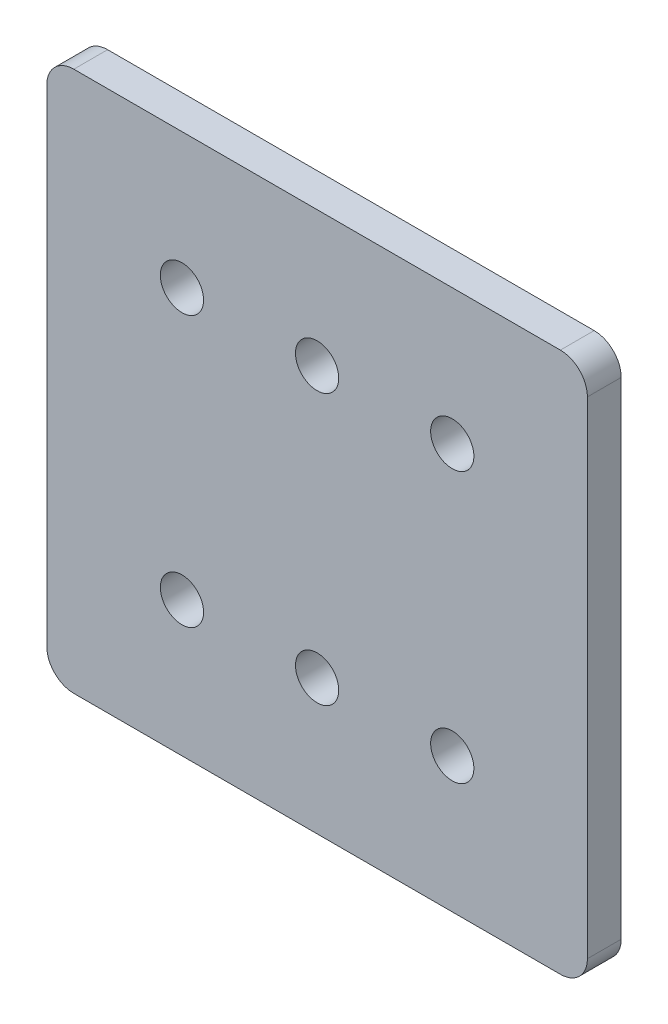
SolidWorks part; units mm, degrees
ref_plane "Front Plane" through (0, 0, 0) normal (0, 0, 1) x (1, 0, 0)
ref_plane "Top Plane" through (0, 0, 0) normal (0, 1, 0) x (1, 0, 0)
ref_plane "Right Plane" through (0, 0, 0) normal (1, 0, 0) x (0, 0, -1)
sketch "Sketch1" plane through (0, 0, 0) normal (0, 0, 1) x (1, 0, 0)
  line L1 (-25.4, -25.4) -> (25.4, -25.4)
  line L2 (-25.4, -25.4) -> (-25.4, 25.4)
  line L3 (-25.4, 25.4) -> (25.4, 25.4)
  line L4 (25.4, -25.4) -> (25.4, 25.4)
  line L5 (-25.4, -25.4) -> (25.4, 25.4) construction
  line L6 (-25.4, 25.4) -> (25.4, -25.4) construction
  point P0 (0, 0)
  dimension "D1" = 50.8
  dimension "D2" = 50.8
extrude "Boss-Extrude1" add sketch "Sketch1" along normal mid plane 3.175
fillet "Fillet1" radius 2.54 4 edges at (25.4, -25.4, 0) (-25.4, -25.4, 0) (25.4, 25.4, 0) (-25.4, 25.4, 0)
sketch "Sketch2" plane through (0, 0, 1.5875) normal (0, 0, 1) x (1, 0, 0)
  line L0 (22.86, 25.4) -> (-22.86, 25.4) construction
  line L1 (-25.4, 22.86) -> (-25.4, -22.86) construction
  line L2 (0, 0) -> (25.4, 0) construction
  line L3 (25.4, -22.86) -> (25.4, 22.86) construction
  circle A0 centre (-12.7, 12.7) radius 2.032
  circle A1 centre (0, 12.7) radius 2.032
  circle A2 centre (12.7, 12.7) radius 2.032
  circle A3 centre (12.7, -12.7) radius 2.032
  circle A4 centre (0, -12.7) radius 2.032
  circle A5 centre (-12.7, -12.7) radius 2.032
  dimension "D1" = 4.064
  dimension "D2" = 12.7
  dimension "D3" = 12.7
  dimension "D4" = 3
extrude "Cut-Extrude1" cut sketch "Sketch2" against normal through all
